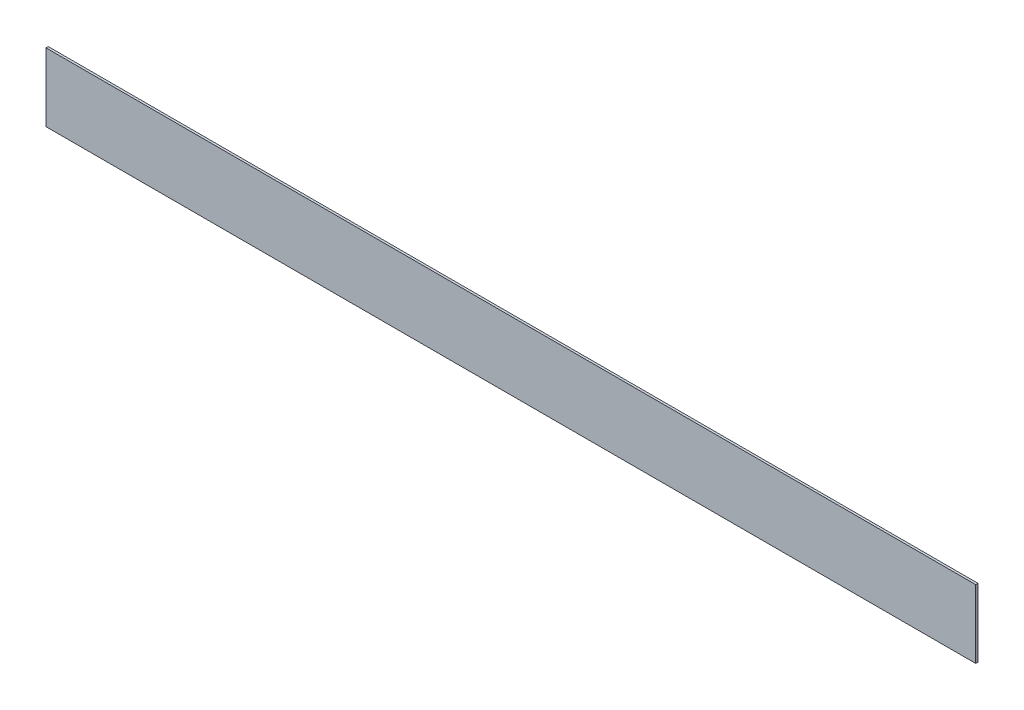
SolidWorks part; units mm, degrees
ref_plane "前视基准面" through (0, 0, 0) normal (0, 0, 1) x (1, 0, 0)
ref_plane "上视基准面" through (0, 0, 0) normal (0, 1, 0) x (1, 0, 0)
ref_plane "右视基准面" through (0, 0, 0) normal (1, 0, 0) x (0, 0, -1)
other "Configuration Table"
sketch "草图1" plane through (0, 0, 0) normal (0, 0, 1) x (1, 0, 0)
  line L1 (0, 0) -> (2056, 0)
  line L2 (0, 0) -> (0, 151)
  line L3 (0, 151) -> (2056, 151)
  line L4 (2056, 0) -> (2056, 151)
  dimension "D1" = 151
  dimension "D2" = 2056
extrude "凸台-拉伸1" add sketch "草图1" along normal blind 5
